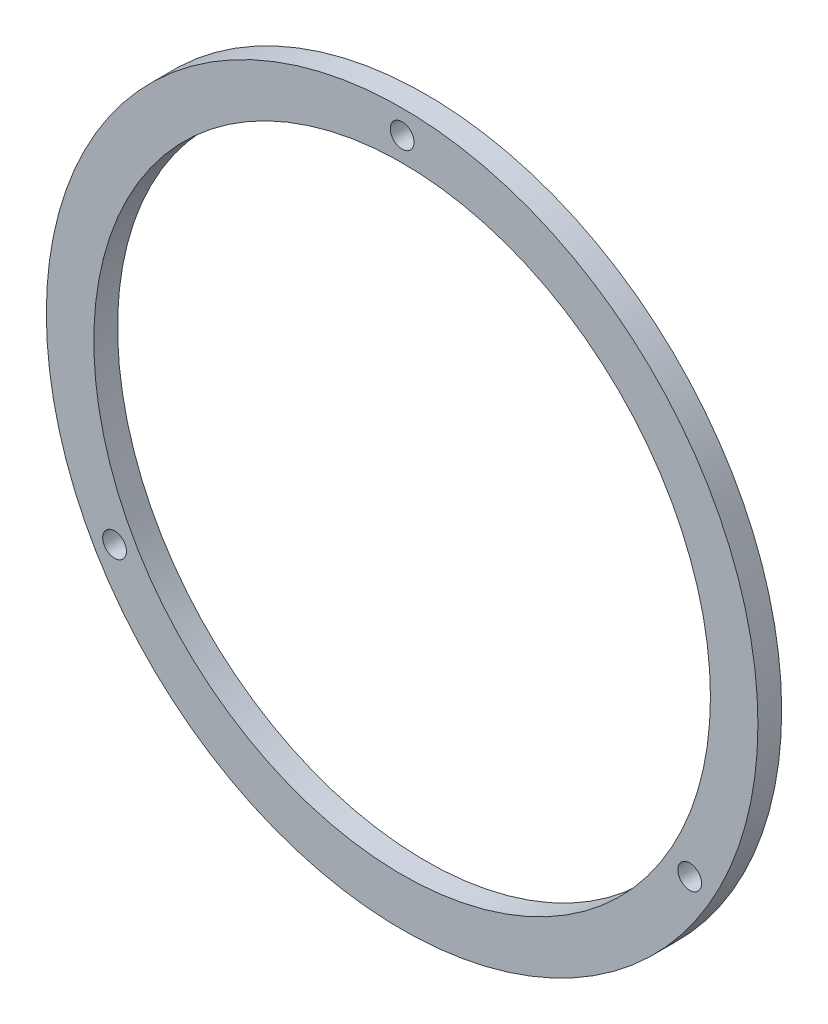
SolidWorks part; units mm, degrees
material "S-Glass Fiber"
ref_plane "Front Plane" through (0, 0, 0) normal (0, 0, 1) x (1, 0, 0)
ref_plane "Top Plane" through (0, 0, 0) normal (0, 1, 0) x (1, 0, 0)
ref_plane "Right Plane" through (0, 0, 0) normal (1, 0, 0) x (0, 0, -1)
sketch "Sketch1" plane through (0, 0, 0) normal (0, 0, 1) x (1, 0, 0)
  circle A0 centre (0, 0) radius 82.4281
  circle A1 centre (0, 0) radius 95.123
  dimension "D1" = 164.8562
  dimension "D2" = 190.246
extrude "Boss-Extrude1" add sketch "Sketch1" along normal blind 6.35
sketch "Sketch2" plane through (0, 0, 6.35) normal (0, 0, 1) x (1, 0, 0)
  line L0 (0, 0) -> (0, 88.773) construction
  circle A0 centre (0, 88.773) radius 3.175
  circle A1 centre (76.8797, -44.3865) radius 3.175
  circle A2 centre (-76.8797, -44.3865) radius 3.175
  point P12 (0, 0)
  dimension "D2" = 6.35
  dimension "D1" = 88.773
  dimension "D3" = 3
extrude "Cut-Extrude1" cut sketch "Sketch2" against normal through all
